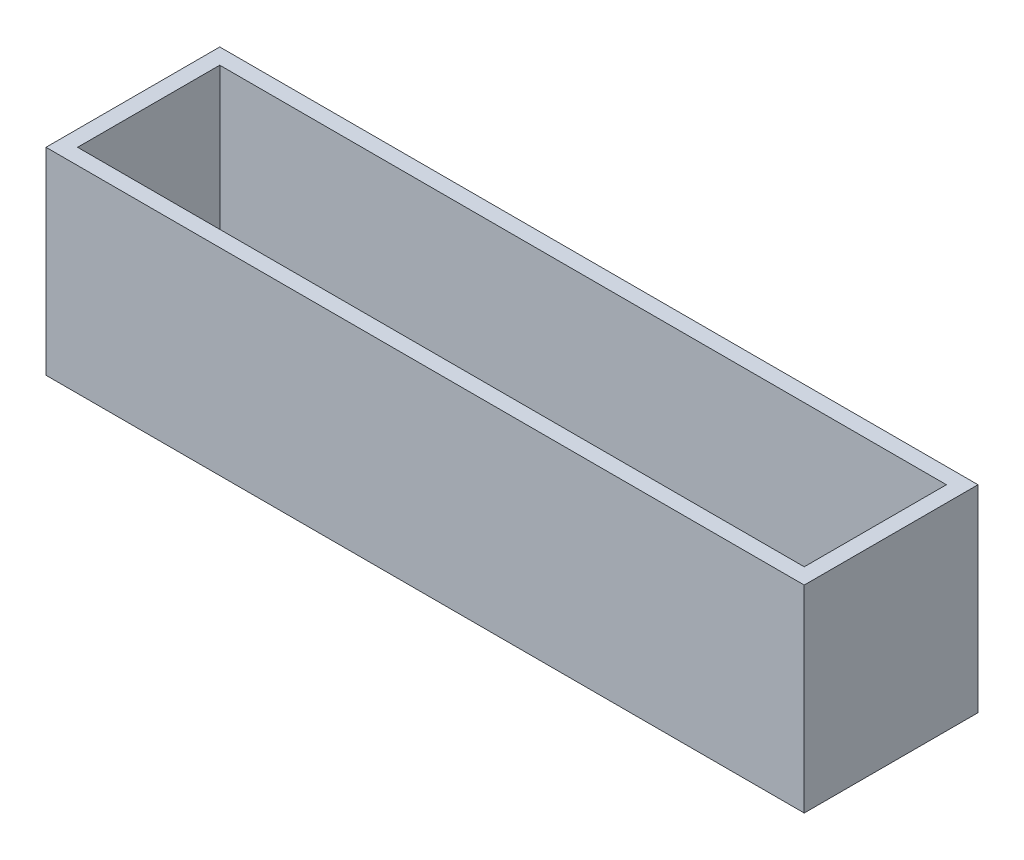
SolidWorks part; units mm, degrees
ref_plane "Front Plane" through (0, 0, 0) normal (0, 0, 1) x (1, 0, 0)
ref_plane "Top Plane" through (0, 0, 0) normal (0, 1, 0) x (1, 0, 0)
ref_plane "Right Plane" through (0, 0, 0) normal (1, 0, 0) x (0, 0, -1)
sketch "Sketch1" plane through (0, 0, 0) normal (0, 1, 0) x (1, 0, 0)
  line L1 (-152.4, -34.925) -> (152.4, -34.925)
  line L2 (-152.4, -34.925) -> (-152.4, 34.925)
  line L3 (-152.4, 34.925) -> (152.4, 34.925)
  line L4 (152.4, -34.925) -> (152.4, 34.925)
  line L5 (0, 34.925) -> (0, -34.925) construction
  line L6 (-152.4, 0) -> (152.4, 0) construction
  point P0 (0, 0)
  dimension "D1" = 304.8
  dimension "D2" = 69.85
extrude "Boss-Extrude1" add sketch "Sketch1" along normal blind 3.175
sketch "Sketch2" plane through (0, 3.175, 0) normal (0, 1, 0) x (1, 0, 0)
  line L0 (146.05, -28.575) -> (146.05, 28.575)
  line L1 (146.05, 28.575) -> (-146.05, 28.575)
  line L2 (-146.05, 28.575) -> (-146.05, -28.575)
  line L3 (-146.05, -28.575) -> (146.05, -28.575)
  line L4 (152.4, -34.925) -> (152.4, 34.925)
  line L5 (152.4, 34.925) -> (-152.4, 34.925)
  line L6 (-152.4, 34.925) -> (-152.4, -34.925)
  line L7 (-152.4, -34.925) -> (152.4, -34.925)
  line L8 (152.4, -34.925) -> (152.4, 34.925)
  line L9 (152.4, 34.925) -> (-152.4, 34.925)
  line L10 (-152.4, 34.925) -> (-152.4, -34.925)
  line L11 (-152.4, -34.925) -> (152.4, -34.925)
  dimension "D1" = 0
  dimension "D2" = 6.35
extrude "Boss-Extrude2" add sketch "Sketch2" along normal blind 76.2
